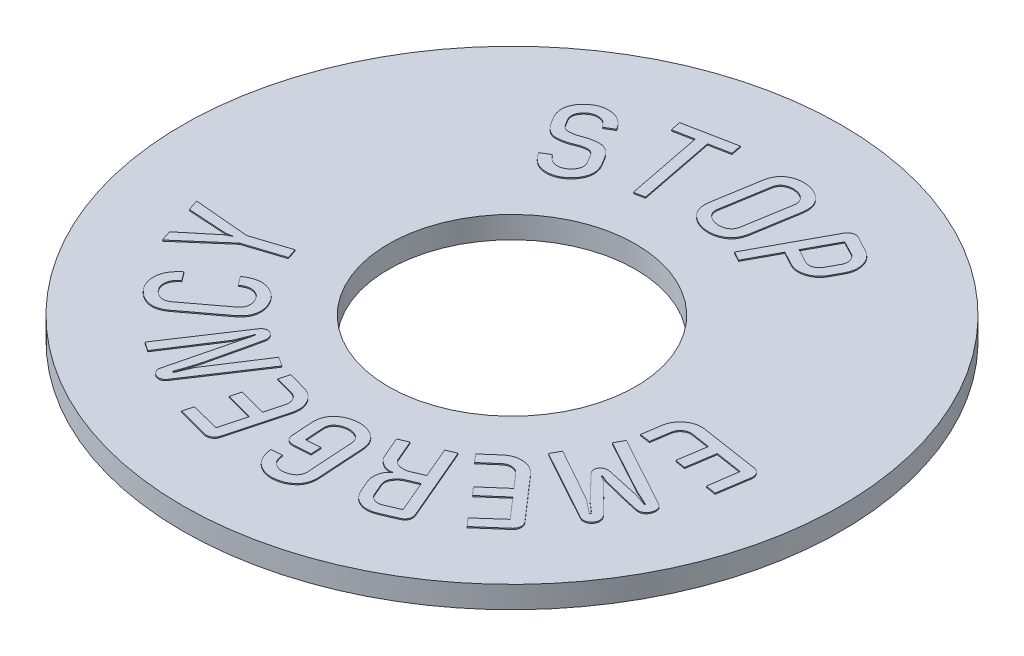
SolidWorks part; units mm, degrees
ref_plane "Front Plane" through (0, 0, 0) normal (0, 0, 1) x (1, 0, 0)
ref_plane "Top Plane" through (0, 0, 0) normal (0, 1, 0) x (1, 0, 0)
ref_plane "Right Plane" through (0, 0, 0) normal (1, 0, 0) x (0, 0, -1)
sketch "Sketch1" plane through (0, 0, 0) normal (0, 1, 0) x (1, 0, 0)
  circle A0 centre (0, 0) radius 30
  circle A1 centre (0, 0) radius 11.25
  circle A2 centre (0, 0) radius 15.8998 construction
  text T0 "EMERGENCY     STOP" font "Zag Bold" height 8
  dimension "D1" = 60
  dimension "D2" = 22.5
extrude "Boss-Extrude1" add sketch "Sketch1" along normal blind 2 contours A0 A1
sketch "Sketch3" plane through (0, 2, 0) normal (0, 1, 0) x (1, 0, 0)
  circle A0 centre (0, 0) radius 30 construction
  circle A1 centre (0, 0) radius 11.25 construction
  circle A2 centre (0, 0) radius 15.8998 construction
  text T0 "EMERGENCY     STOP" font "Zag Bold" height 8
  point P4 (0, 0)
extrude "Boss-Extrude2" add sketch "Sketch3" along normal blind 0.1
